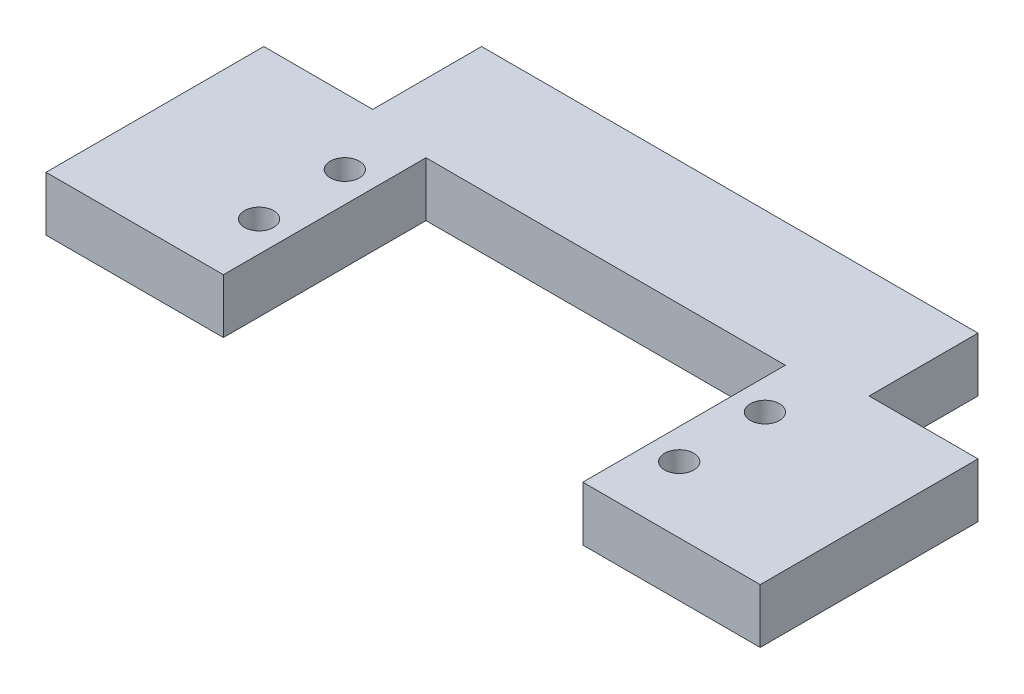
SolidWorks part; units mm, degrees
material "Acrylic (Medium-high impact)"
ref_plane "Front Plane" through (0, 0, 0) normal (0, 0, 1) x (1, 0, 0)
ref_plane "Top Plane" through (0, 0, 0) normal (0, 1, 0) x (1, 0, 0)
ref_plane "Right Plane" through (0, 0, 0) normal (1, 0, 0) x (0, 0, -1)
sketch "Sketch1" plane through (0, 0, 0) normal (0, 1, 0) x (1, 0, 0)
  line L0 (-6.35, 25.4) -> (6.35, 25.4)
  line L1 (-20.955, -10.922) -> (20.955, -10.922)
  line L2 (-20.955, -10.922) -> (-20.955, 10.922)
  line L3 (-20.955, 10.922) -> (20.955, 10.922)
  line L4 (20.955, -10.922) -> (20.955, 10.922)
  line L5 (-20.955, -10.922) -> (20.955, 10.922) construction
  line L6 (-20.955, 10.922) -> (20.955, -10.922) construction
  line L7 (24.4996, -5) -> (-24.4996, -5) construction
  line L8 (24.4996, -5) -> (24.4996, 5) construction
  line L9 (24.4996, 5) -> (-24.4996, 5) construction
  line L10 (-24.4996, -5) -> (-24.4996, 5) construction
  line L11 (24.4996, -5) -> (-24.4996, 5) construction
  line L12 (24.4996, 5) -> (-24.4996, -5) construction
  line L13 (41.6458, -25.4) -> (-41.6458, -25.4) construction
  line L14 (41.6458, -25.4) -> (41.6458, 25.4) construction
  line L15 (41.6458, 25.4) -> (-41.6458, 25.4) construction
  line L16 (-41.6458, -25.4) -> (-41.6458, 25.4) construction
  line L17 (41.6458, -25.4) -> (-41.6458, 25.4) construction
  line L18 (41.6458, 25.4) -> (-41.6458, -25.4) construction
  line L19 (-28.9458, 25.4) -> (-6.35, 25.4)
  line L20 (-6.35, -25.4) -> (6.35, -25.4)
  line L21 (-28.9458, 25.4) -> (-28.9458, 12.7)
  line L22 (-41.6458, 25.4) -> (-28.9458, 25.4) construction
  line L23 (-41.6458, 25.4) -> (-41.6458, 12.7) construction
  line L24 (-41.6458, 12.7) -> (-28.9458, 12.7) construction
  line L25 (-28.9458, 25.4) -> (-28.9458, 12.7) construction
  line L26 (-28.9458, -12.7) -> (-28.9458, -25.4)
  line L27 (-28.9458, -25.4) -> (-6.35, -25.4)
  line L28 (6.35, -25.4) -> (28.9458, -25.4)
  line L29 (6.35, 25.4) -> (28.9458, 25.4)
  line L30 (28.9458, 25.4) -> (28.9458, 12.7)
  line L31 (-28.9458, 12.7) -> (-41.6458, 12.7)
  line L32 (-41.6458, 0) -> (41.6458, 0) construction
  line L33 (28.9458, -12.7) -> (28.9458, -25.4)
  line L34 (-28.9458, -12.7) -> (-41.6458, -12.7)
  line L35 (-41.6458, 12.7) -> (-41.6458, -12.7)
  line L36 (28.9458, 12.7) -> (41.6458, 12.7)
  line L38 (28.9458, -12.7) -> (41.6458, -12.7)
  line L39 (41.6458, 12.7) -> (41.6458, -12.7)
  line L46 (-41.6458, -25.4) -> (-6.35, -25.4) construction
  line L47 (6.35, -25.4) -> (41.6458, -25.4) construction
  line L75 (-41.6458, 25.4) -> (-6.35, 25.4) construction
  line L76 (6.35, 25.4) -> (41.6458, 25.4) construction
  circle A0 centre (-24.4996, 5) radius 1.7005
  circle A1 centre (-24.4996, -5) radius 1.7005
  circle A2 centre (24.4996, -5) radius 1.7005
  circle A3 centre (24.4996, 5) radius 1.7005
  point P0 (0, 0)
  point P6 (0, 0)
  point P11 (0, 0)
  dimension "D7" = 3.4011
  dimension "D1" = 41.91
  dimension "D2" = 21.844
  dimension "D3" = 48.9991
  dimension "D4" = 10
  dimension "D5" = 83.2917
  dimension "D6" = 50.8
  dimension "D8" = 12.7
  dimension "D9" = 12.7
  dimension "D10" = 12.7
  dimension "D11" = 12.7
  dimension "D12" = 12.7
  dimension "D13" = 12.7
  dimension "D14" = 12.7
  dimension "D15" = 12.7
extrude "Boss-Extrude1" add sketch "Sketch1" along normal blind 6.35
sketch "Sketch2" plane through (0, 6.35, 0) normal (0, 1, 0) x (1, 0, 0)
  line L0 (-28.9458, -12.7) -> (-20.955, -12.7)
  line L1 (-28.9458, -25.4) -> (28.9458, -25.4)
  line L2 (-28.9458, -25.4) -> (-28.9458, -12.7)
  line L3 (-20.955, -12.7) -> (-20.955, -10.922)
  line L4 (28.9458, -25.4) -> (28.9458, -12.7)
  line L5 (-20.955, -10.922) -> (20.955, -10.922)
  line L6 (20.955, -10.922) -> (20.955, -12.7)
  line L7 (20.955, -12.7) -> (28.9458, -12.7)
  line L8 (-41.6458, -12.7) -> (-28.9458, -12.7) construction
extrude "Cut-Extrude1" cut sketch "Sketch2" against normal through all
